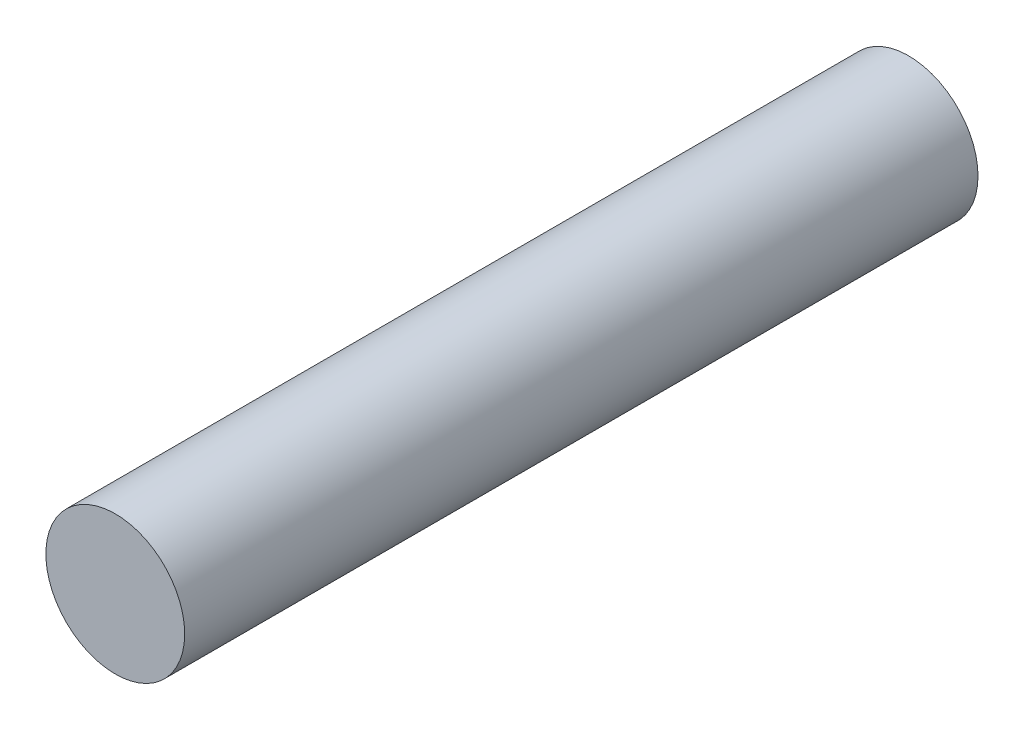
SolidWorks part; units mm, degrees
ref_plane "前视基准面" through (0, 0, 0) normal (0, 0, 1) x (1, 0, 0)
ref_plane "上视基准面" through (0, 0, 0) normal (0, 1, 0) x (1, 0, 0)
ref_plane "右视基准面" through (0, 0, 0) normal (1, 0, 0) x (0, 0, -1)
other "Configuration Table"
sketch "草图1" plane through (0, 0, 0) normal (0, 0, 1) x (1, 0, 0)
  circle A0 centre (0, 0) radius 1.75
  dimension "D1" = 3.5
extrude "凸台-拉伸1" add sketch "草图1" along normal blind 20
